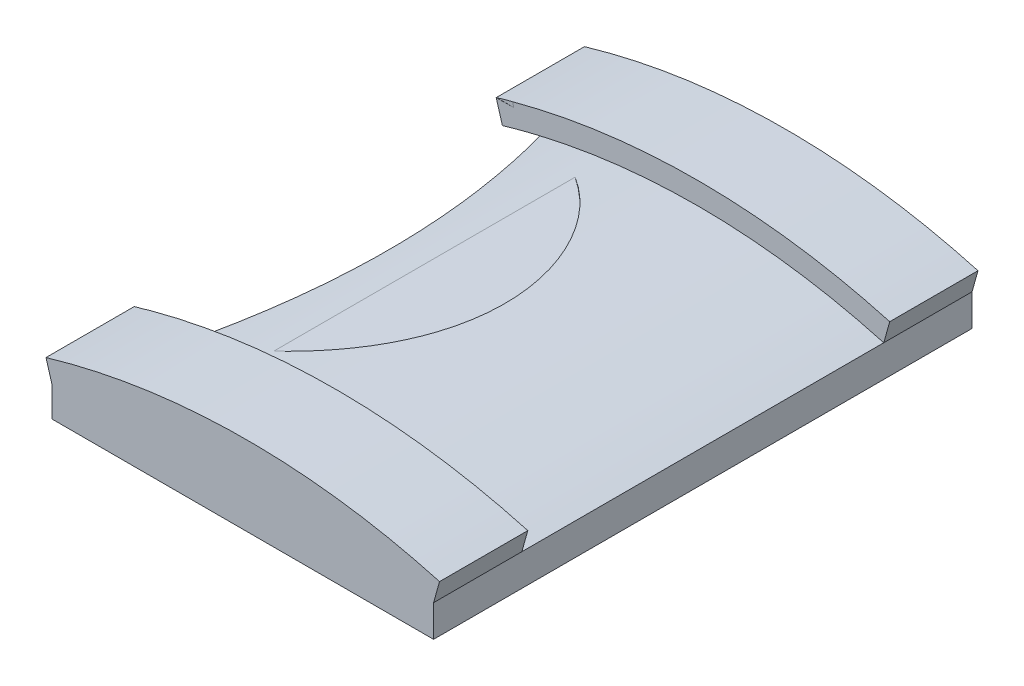
SolidWorks part; units mm, degrees
material "CA"
ref_plane "Front Plane" through (0, 0, 0) normal (0, 0, 1) x (1, 0, 0)
ref_plane "Top Plane" through (0, 0, 0) normal (0, 1, 0) x (1, 0, 0)
ref_plane "Right Plane" through (0, 0, 0) normal (1, 0, 0) x (0, 0, -1)
sketch "Sketch1" plane through (0, 0, 0) normal (0, 0, 1) x (1, 0, 0)
  line L0 (-89.8245, 33.3888) -> (-89.8245, -2.6112)
  line L1 (-89.8245, -2.6112) -> (342.1755, -2.6112)
  line L2 (342.1755, -2.6112) -> (342.1755, 33.3888)
  line L3 (-89.8245, 33.3888) -> (-89.8245, 63.3888)
  line L4 (342.1755, 33.3888) -> (342.1755, 63.3888)
  line L5 (342.1755, 63.3888) -> (-89.8245, 63.3888)
extrude "Boss-Extrude1" add sketch "Sketch1" along normal blind 610
sketch "Sketch2" plane through (0, 63.3888, 0) normal (0, 1, 0) x (1, 0, 0)
  line L0 (-89.8245, 0) -> (-89.8245, -610)
  arc A0 (-89.8245, 0) -> (-89.8245, -610) centre (-665.895, -305) cw
extrude "Cut-Extrude1" cut sketch "Sketch2" against normal blind 610
sketch "Sketch3" plane through (0, 0, 610) normal (0, 0, 1) x (1, 0, 0)
  line L1 (-89.8245, 63.3888) -> (-89.8245, -2.6112) construction
  line L3 (342.1755, -2.6112) -> (342.1755, 63.3888) construction
  line L4 (-89.8245, 30.3888) -> (-89.8245, 63.3888)
  line L5 (-89.8245, 63.3888) -> (342.1755, 63.3888)
  line L6 (342.1755, 63.3888) -> (342.1755, 33.3888)
  arc A0 (-89.8245, 30.3888) -> (342.1755, 33.3888) centre (131.3897, -718.9642) cw
extrude "Cut-Extrude2" cut sketch "Sketch3" against normal through all
sketch "Sketch4" plane through (0, 0, 610) normal (0, 0, 1) x (1, 0, 0)
  line L0 (-96.9027, 54.3659) -> (-89.8245, 30.3888)
  line L1 (348.92, 57.4619) -> (342.1755, 33.3888)
  arc A0 (-89.8245, 30.3888) -> (342.1755, 33.3888) centre (131.3897, -718.9642) cw
  arc A1 (-96.9027, 54.3659) -> (348.92, 57.4619) centre (131.3897, -718.9642) cw
  dimension "D1" = 25
extrude "Boss-Extrude2" add sketch "Sketch4" against normal blind 100
sketch "Sketch5" plane through (0, 0, 0) normal (0, 0, -1) x (-1, 0, 0)
  line L0 (96.9027, 54.3659) -> (89.8245, 30.3888) construction
  line L1 (-348.92, 57.4619) -> (-342.1755, 33.3888)
  line L2 (89.8245, 30.3888) -> (96.9027, 54.3659)
  arc A0 (-342.1755, 33.3888) -> (89.8245, 30.3888) centre (-131.3897, -718.9642) cw
  arc A1 (-348.92, 57.4619) -> (96.9027, 54.3659) centre (-131.3897, -718.9642) cw
  arc A2 (96.9027, 54.3659) -> (-348.92, 57.4619) centre (-131.3897, -718.9642) ccw construction
extrude "Boss-Extrude3" add sketch "Sketch5" against normal blind 100
sketch "Sketch6" plane through (-74.3722, -21.9552, 0) normal (-0.9591, -0.2831, 0) x (0, 0, 1)
  line L0 (100, 79.5772) -> (510, 79.5772)
  arc A0 (100, 79.5772) -> (510, 79.5772) centre (305, 89.3282) cw
revolve "Cut-Revolve3" cut sketch "Sketch6" angle 106 about L0
